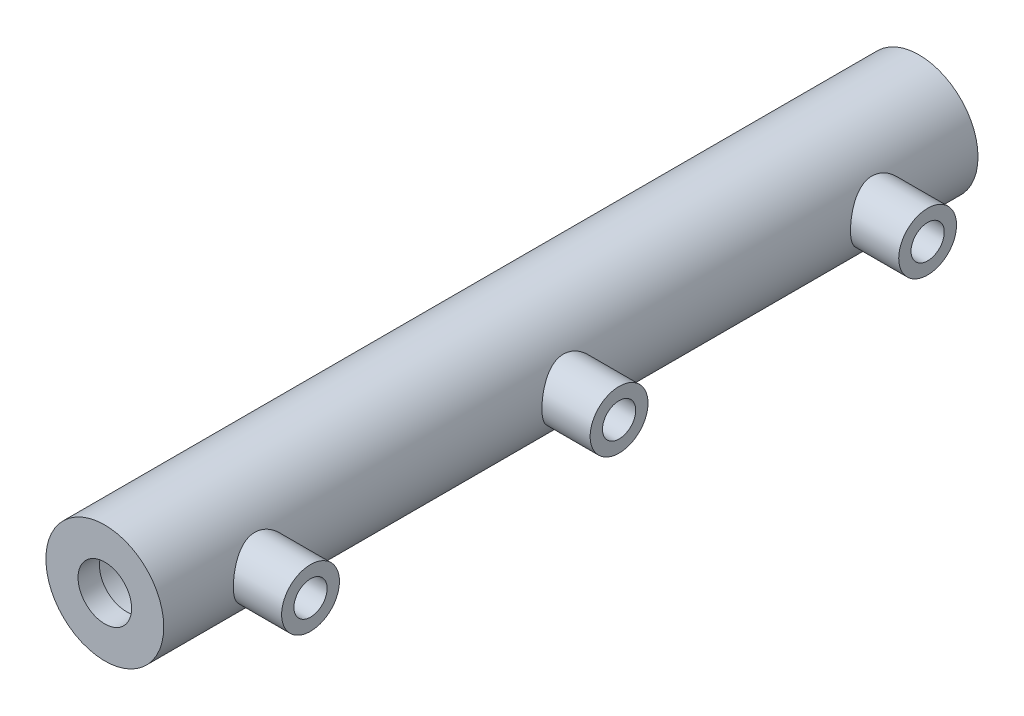
SolidWorks part; units mm, degrees
material "45"
ref_plane "前视基准面" through (0, 0, 0) normal (0, 0, 1) x (1, 0, 0)
ref_plane "上视基准面" through (0, 0, 0) normal (0, 1, 0) x (1, 0, 0)
ref_plane "右视基准面" through (0, 0, 0) normal (1, 0, 0) x (0, 0, -1)
sketch "草图3" plane through (0, 0, 0) normal (0, 0, 1) x (1, 0, 0)
  line L0 (0, 0) -> (0, 54.4339) construction
  line L4 (0, 0) -> (-52.1482, 0) construction
  circle A1 centre (0, 0) radius 27.5
  circle A2 centre (0, 0) radius 20
  dimension "D1" = 55
  dimension "D2" = 40
extrude "凸台-拉伸1" add sketch "草图3" along normal mid plane 380
sketch "草图4" plane through (0, 0, 190) normal (0, 0, 1) x (1, 0, 0)
  circle A0 centre (0, 0) radius 27.5 construction
  circle A1 centre (0, 0) radius 27.5
  circle A2 centre (0, 0) radius 12.5
  dimension "D1" = 25
extrude "凸台-拉伸2" add sketch "草图4" against normal blind 10
sketch "草图5" plane through (0, 0, -190) normal (0, 0, -1) x (-1, 0, 0)
  circle A0 centre (0, 0) radius 27.5 construction
  circle A1 centre (0, 0) radius 27.5
  circle A2 centre (0, 0) radius 12.5
  dimension "D1" = 25
extrude "凸台-拉伸3" add sketch "草图5" against normal blind 10
ref_plane "基准面1" through (50, 0, 0) normal (1, 0, 0) x (0, 0, -1)
sketch "草图6" plane through (50, 0, 0) normal (1, 0, 0) x (0, 0, -1)
  line L0 (0, 0) -> (-198.7972, 0) construction
  line L1 (0, 0) -> (211.4112, 0) construction
  line L2 (0, 0) -> (0, 58.9528) construction
  circle A0 centre (0, 0) radius 13.5
  circle A1 centre (-144, 0) radius 13.5
  circle A2 centre (144, 0) radius 13.5
  dimension "D1" = 27
  dimension "D2" = 27
  dimension "D3" = 288
extrude "凸台-拉伸4" add sketch "草图6" against normal up to surface (22.5 mm away) up to face at (27.5, 0, -190)
hole_wizard "M18 螺纹孔1" positions "3D草图2" profile "草图8" tap size "M18" standard "GB"
sketch3d "3D草图2"
  line L0 (27.5, 0, 144) -> (50, 0, 144) construction
  line L1 (27.5, 0, -144) -> (50, 0, -144) construction
  line L2 (27.5, 0, 0) -> (50, 0, 0) construction
  point P0 (50, 0, 144)
  point P4 (50, 0, 0)
  point P6 (50, 0, -144)
sketch "草图8" plane through (50, 0, 144) normal (0, 1, 0) x (0, 0, -1)
  line L0 (0, 0) -> (0, 53.1567)
  line L1 (0, 53.1567) -> (7.75, 48.5)
  line L2 (7.75, 48.5) -> (7.75, 0)
  line L5 (7.75, 0) -> (0, 0)
  line L10 (0, 53.1567) -> (-7.75, 48.5) construction
  line L11 (0, -6.35) -> (0, 107.95) construction
  dimension "螺纹孔钻头直径" = 15.5
  dimension "螺纹孔钻头深度" = 48.5
  dimension "导头角度" = 118
cosmetic thread "孔螺蚊线1" parameters "D1"=31.5626, "D2"=18
cosmetic thread "孔螺蚊线2" parameters "D1"=31.5626, "D2"=18
cosmetic thread "孔螺蚊线3" parameters "D1"=31.5626, "D2"=18
ref_plane "基准面2" [suppressed] through (0, 0, 157) normal (0, 0, 1) x (1, 0, 0)
sketch "草图9" [suppressed] plane through (0, 0, 157) normal (0, 0, 1) x (1, 0, 0)
  line L0 (-47.5, -15) -> (-47.5, -65)
  line L1 (-47.5, -65) -> (47.5, -65)
  line L2 (47.5, -65) -> (47.5, -15)
  line L3 (47.5, -15) -> (23.0489, -15)
  line L4 (0, 0) -> (0, -65) construction
  line L5 (-23.0489, -15) -> (-47.5, -15)
  circle A0 centre (0, 0) radius 12.5 construction
  circle A1 centre (0, 0) radius 27.5
  arc A2 (-23.0489, -15) -> (23.0489, -15) centre (0, 0) ccw
  dimension "D4" = 15
  dimension "D2" = 95
  dimension "D3" = 50
  dimension "D1" = 0
extrude "凸台-拉伸5" [suppressed] add sketch "草图9" against normal blind 8
sketch "草图10" [suppressed] plane through (0, 0, 157) normal (0, 0, 1) x (1, 0, 0)
  line L0 (-35, -52.5) -> (35, -52.5) construction
  line L1 (0, 0) -> (0, -52.5) construction
  circle A0 centre (-35, -52.5) radius 5
  circle A1 centre (35, -52.5) radius 5
  circle A2 centre (0, 0) radius 12.5 construction
  dimension "D1" = 70
  dimension "D2" = 52.5
  dimension "D3" = 10
extrude "切除-拉伸1" [suppressed] cut sketch "草图10" against normal up to next
fillet "圆角1" [suppressed] radius 10
chamfer "倒角1" [suppressed] distance 20 angle 45
mirror "镜向1" [suppressed] about plane through (0, 0, 0) normal (0, 0, 1)
